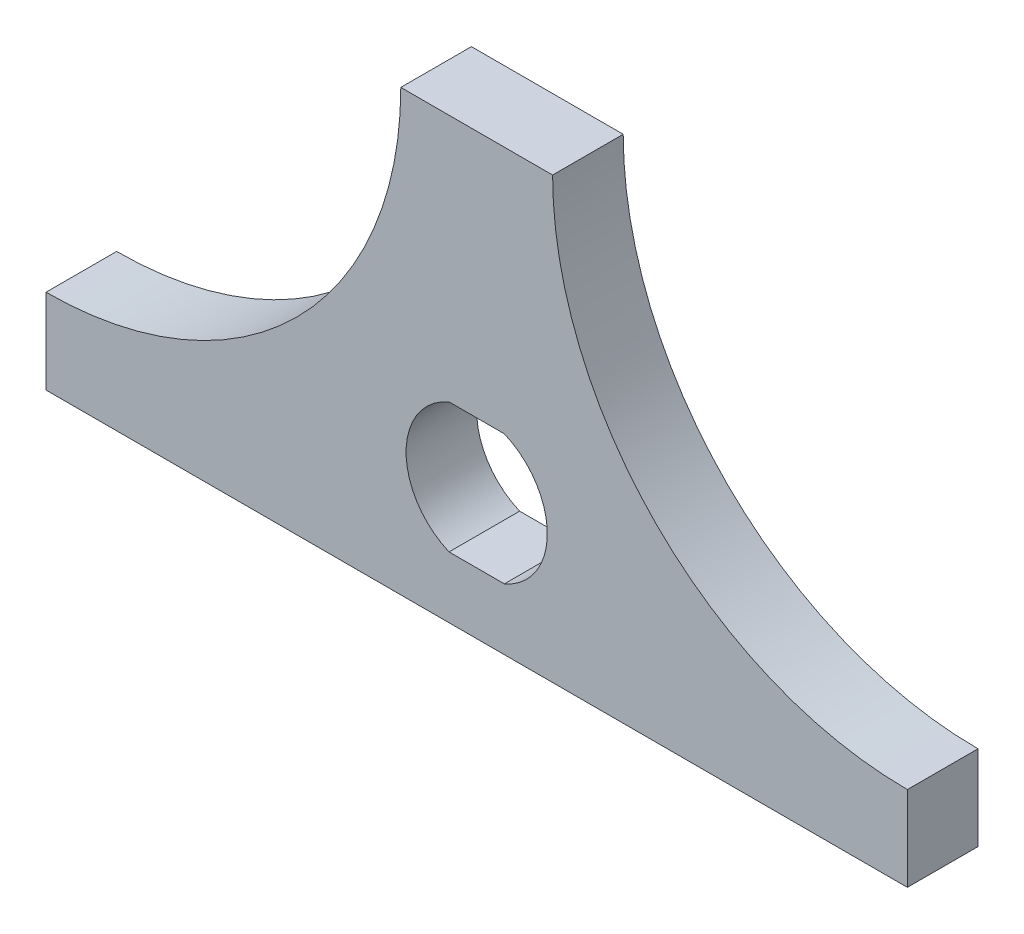
SolidWorks part; units mm, degrees
ref_plane "Front Plane" through (0, 0, 0) normal (0, 0, 1) x (1, 0, 0)
ref_plane "Top Plane" through (0, 0, 0) normal (0, 1, 0) x (1, 0, 0)
ref_plane "Right Plane" through (0, 0, 0) normal (1, 0, 0) x (0, 0, -1)
sketch "Sketch1" plane through (0, 0, 0) normal (0, 0, 1) x (1, 0, 0)
  line L1 (-64.7815, -40.5494) -> (64.7815, -40.5494)
  line L2 (-64.7815, -40.5494) -> (-64.7815, 40.5494)
  line L3 (-64.7815, 40.5494) -> (64.7815, 40.5494)
  line L4 (64.7815, -40.5494) -> (64.7815, 40.5494)
  line L5 (-64.7815, -40.5494) -> (64.7815, 40.5494) construction
  line L6 (-64.7815, 40.5494) -> (64.7815, -40.5494) construction
  point P0 (0, 0)
extrude "Boss-Extrude1" add sketch "Sketch1" along normal blind 6.35
sketch "Sketch2" plane through (0, 0, 6.35) normal (0, 0, 1) x (1, 0, 0)
  circle A0 centre (0, 0) radius 6.35
  dimension "D1" = 12.7
extrude "Cut-Extrude1" cut sketch "Sketch2" against normal through all
sketch "Sketch4" plane through (0, 0, 6.35) normal (0, 0, 1) x (1, 0, 0)
  line L0 (38.735, 28.1699) -> (38.735, -11.3588) construction
  line L1 (-38.735, -11.3588) -> (38.735, -11.3588)
  line L2 (-38.735, 28.1699) -> (-38.735, -11.3588) construction
  line L3 (-38.735, 28.1699) -> (-6.8263, 28.1699) construction
  line L4 (-6.8263, 28.1699) -> (6.8263, 28.1699)
  line L5 (-38.735, -3.7388) -> (-38.735, -11.3588)
  line L6 (38.735, -11.3588) -> (38.735, -3.7388)
  circle A0 centre (-38.735, 28.1699) radius 31.9088 construction
  circle A1 centre (38.735, 28.1699) radius 31.9088 construction
  arc A2 (-6.8263, 28.1699) -> (-38.735, -3.7388) centre (-38.735, 28.1699) cw
  arc A3 (6.8263, 28.1699) -> (38.735, -3.7388) centre (38.735, 28.1699) ccw
  dimension "D1" = 63.8175
  dimension "D2" = 7.62
extrude "Cut-Extrude2" cut sketch "Sketch4" against normal through all flip side to cut
sketch "Sketch6" plane through (0, 0, 6.35) normal (0, 0, 1) x (1, 0, 0)
  line L0 (-2.4887, 5.842) -> (2.4887, 5.842)
  line L1 (-2.4887, 5.842) -> (-2.4887, 7.112)
  line L2 (-2.4887, 7.112) -> (2.4887, 7.112)
  line L3 (2.4887, 7.112) -> (2.4887, 5.842)
  circle A0 centre (0, 0) radius 6.35 construction
  dimension "D1" = 5.842
  dimension "D2" = 1.27
extrude "Boss-Extrude2" add sketch "Sketch6" against normal up to surface (6.35 mm away) up to face at (0, 2.1546, 0)
mirror "Mirror1" about plane through (0, 0, 0) normal (0, 1, 0) of "Boss-Extrude2"
equation "\"D1@Sketch6\"=(0.45/2)+0.005"
